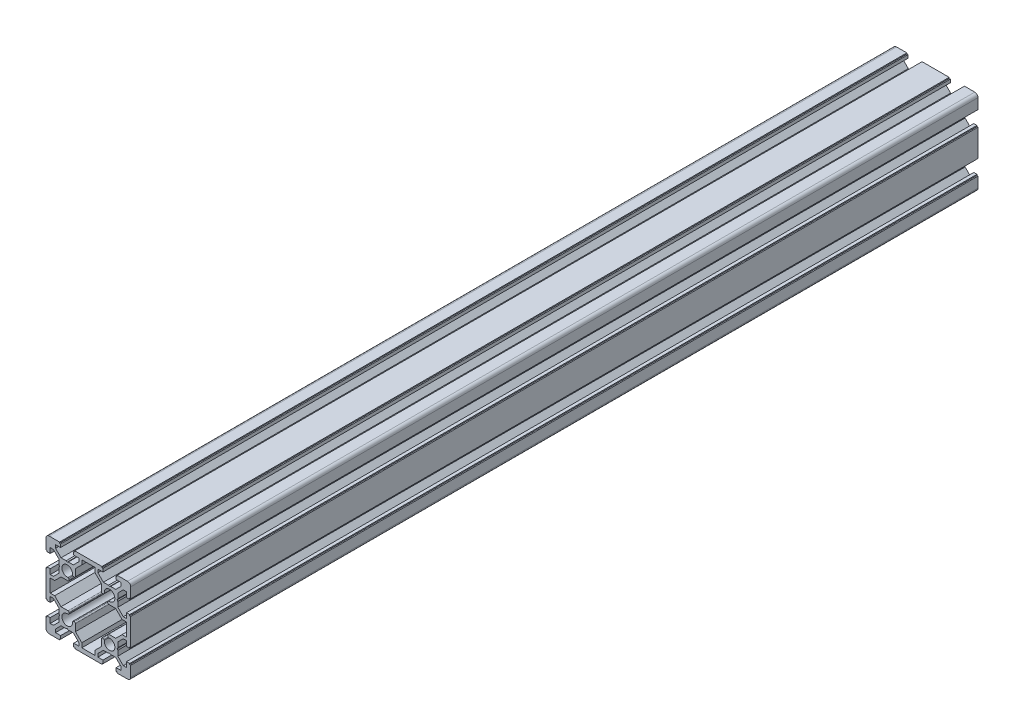
SolidWorks part; units mm, degrees
ref_plane "前视基准面" through (0, 0, 0) normal (0, 0, 1) x (1, 0, 0)
ref_plane "上视基准面" through (0, 0, 0) normal (0, 1, 0) x (1, 0, 0)
ref_plane "右视基准面" through (0, 0, 0) normal (1, 0, 0) x (0, 0, -1)
sketch "草图29" plane through (0, 0, 0) normal (0, 0, 1) x (1, 0, 0)
  line B0 (0, 24.9728) -> (0, 15.0272) construction
  line B1 (-11.0182, 10) -> (30.6964, 10) construction
  line B2 (20, 24.9728) -> (20, 15.0272) construction
  line B3 (20, 4.9728) -> (20, -4.9728) construction
  line B4 (15.0272, 0) -> (24.9728, 0) construction
  line B5 (0, 4.9728) -> (0, -4.9728) construction
  line B6 (-4.9728, 0) -> (4.9728, 0) construction
  line B7 (15.0272, 20) -> (24.9728, 20) construction
  line B8 (-4.9728, 20) -> (4.9728, 20) construction
  line B9 (28, 6.9) -> (25.9101, 6.9)
  line B10 (25.9101, 6.9) -> (22.9101, 3.9)
  line B11 (22.9101, 3.9) -> (19.6066, 3.9)
  line B12 (19.1236, 3.2706) -> (19.2795, 2.689)
  line B13 (17.311, 0.7205) -> (16.7294, 0.8764)
  line B14 (16.1, 0.3934) -> (16.1, -2.9101)
  line B15 (16.1, -2.9101) -> (13.1, -5.9101)
  line B16 (13.1, -5.9101) -> (13.1, -8)
  line B17 (13.1, -8) -> (6.9, -8)
  line B18 (6.9, -8) -> (6.9, -5.9101)
  line B19 (6.9, -5.9101) -> (3.9, -2.9101)
  line B20 (3.9, -2.9101) -> (3.9, 0.3934)
  line B21 (3.2706, 0.8764) -> (2.689, 0.7205)
  line B22 (0.7205, 2.689) -> (0.8764, 3.2706)
  line B23 (0.3934, 3.9) -> (-2.9101, 3.9)
  line B24 (-2.9101, 3.9) -> (-5.9101, 6.9)
  line B25 (-5.9101, 6.9) -> (-8, 6.9)
  line B26 (-8, 6.9) -> (-8, 13.1)
  line B27 (-8, 13.1) -> (-5.9101, 13.1)
  line B28 (-5.9101, 13.1) -> (-2.9101, 16.1)
  line B29 (-2.9101, 16.1) -> (0.3934, 16.1)
  line B30 (0.8764, 16.7294) -> (0.7205, 17.311)
  line B31 (2.689, 19.2795) -> (3.2706, 19.1236)
  line B32 (3.9, 19.6066) -> (3.9, 22.9101)
  line B33 (3.9, 22.9101) -> (6.9, 25.9101)
  line B34 (6.9, 25.9101) -> (6.9, 28)
  line B35 (6.9, 28) -> (13.1, 28)
  line B36 (13.1, 28) -> (13.1, 25.9101)
  line B37 (13.1, 25.9101) -> (16.1, 22.9101)
  line B38 (16.1, 22.9101) -> (16.1, 19.6066)
  line B39 (16.7294, 19.1236) -> (17.311, 19.2795)
  line B40 (19.2795, 17.311) -> (19.1236, 16.7294)
  line B41 (19.6066, 16.1) -> (22.9101, 16.1)
  line B42 (22.9101, 16.1) -> (25.9101, 13.1)
  line B43 (25.9101, 13.1) -> (28, 13.1)
  line B44 (28, 13.1) -> (28, 6.9)
  line B45 (0.5196, -3.9) -> (2.9101, -3.9)
  line B46 (2.9101, -3.9) -> (5.5, -6.4899)
  line B47 (5.5, -6.4899) -> (5.5, -8)
  line B48 (5.5, -8) -> (3.1, -8)
  line B49 (3.1, -8) -> (3.1, -9.5)
  line B50 (3.1, -9.5) -> (3.6, -9.5)
  line B51 (3.6, -9.5) -> (3.6, -10)
  line B52 (3.6, -10) -> (16.4, -10)
  line B53 (16.4, -10) -> (16.4, -9.5)
  line B54 (16.4, -9.5) -> (16.9, -9.5)
  line B55 (16.9, -9.5) -> (16.9, -8)
  line B56 (16.9, -8) -> (14.5, -8)
  line B57 (14.5, -8) -> (14.5, -6.4899)
  line B58 (14.5, -6.4899) -> (17.0899, -3.9)
  line B59 (17.0899, -3.9) -> (19.4804, -3.9)
  line B60 (19.4804, -3.9) -> (20, -3.6)
  line B61 (20, -3.6) -> (20.5196, -3.9)
  line B62 (20.5196, -3.9) -> (22.9101, -3.9)
  line B63 (22.9101, -3.9) -> (25.5, -6.4899)
  line B64 (25.5, -6.4899) -> (25.5, -8)
  line B65 (25.5, -8) -> (23.1, -8)
  line B66 (23.1, -8) -> (23.1, -9.5)
  line B67 (23.1, -9.5) -> (23.6, -9.5)
  line B68 (23.6, -9.5) -> (23.6, -10)
  line B69 (23.6, -10) -> (28.5, -10)
  line B70 (30, -8.5) -> (30, -3.6)
  line B71 (30, -3.6) -> (29.5, -3.6)
  line B72 (29.5, -3.6) -> (29.5, -3.1)
  line B73 (29.5, -3.1) -> (28, -3.1)
  line B74 (28, -3.1) -> (28, -5.5)
  line B75 (28, -5.5) -> (26.4899, -5.5)
  line B76 (26.4899, -5.5) -> (23.9, -2.9101)
  line B77 (23.9, -2.9101) -> (23.9, -0.5196)
  line B78 (23.9, -0.5196) -> (23.6, 0)
  line B79 (23.6, 0) -> (23.9, 0.5196)
  line B80 (23.9, 0.5196) -> (23.9, 2.9101)
  line B81 (23.9, 2.9101) -> (26.4899, 5.5)
  line B82 (26.4899, 5.5) -> (28, 5.5)
  line B83 (28, 5.5) -> (28, 3.1)
  line B84 (28, 3.1) -> (29.5, 3.1)
  line B85 (29.5, 3.1) -> (29.5, 3.6)
  line B86 (29.5, 3.6) -> (30, 3.6)
  line B87 (30, 3.6) -> (30, 16.4)
  line B88 (30, 16.4) -> (29.5, 16.4)
  line B89 (29.5, 16.4) -> (29.5, 16.9)
  line B90 (29.5, 16.9) -> (28, 16.9)
  line B91 (28, 16.9) -> (28, 14.5)
  line B92 (28, 14.5) -> (26.4899, 14.5)
  line B93 (26.4899, 14.5) -> (23.9, 17.0899)
  line B94 (23.9, 17.0899) -> (23.9, 19.4804)
  line B95 (23.9, 19.4804) -> (23.6, 20)
  line B96 (23.6, 20) -> (23.9, 20.5196)
  line B97 (23.9, 20.5196) -> (23.9, 22.9101)
  line B98 (23.9, 22.9101) -> (26.4899, 25.5)
  line B99 (26.4899, 25.5) -> (28, 25.5)
  line B100 (28, 25.5) -> (28, 23.1)
  line B101 (28, 23.1) -> (29.5, 23.1)
  line B102 (29.5, 23.1) -> (29.5, 23.6)
  line B103 (29.5, 23.6) -> (30, 23.6)
  line B104 (30, 23.6) -> (30, 28.5)
  line B105 (28.5, 30) -> (23.6, 30)
  line B106 (23.6, 30) -> (23.6, 29.5)
  line B107 (23.6, 29.5) -> (23.1, 29.5)
  line B108 (23.1, 29.5) -> (23.1, 28)
  line B109 (23.1, 28) -> (25.5, 28)
  line B110 (25.5, 28) -> (25.5, 26.4899)
  line B111 (25.5, 26.4899) -> (22.9101, 23.9)
  line B112 (22.9101, 23.9) -> (20.5196, 23.9)
  line B113 (20.5196, 23.9) -> (20, 23.6)
  line B114 (20, 23.6) -> (19.4804, 23.9)
  line B115 (19.4804, 23.9) -> (17.0899, 23.9)
  line B116 (17.0899, 23.9) -> (14.5, 26.4899)
  line B117 (14.5, 26.4899) -> (14.5, 28)
  line B118 (14.5, 28) -> (16.9, 28)
  line B119 (16.9, 28) -> (16.9, 29.5)
  line B120 (16.9, 29.5) -> (16.4, 29.5)
  line B121 (16.4, 29.5) -> (16.4, 30)
  line B122 (16.4, 30) -> (3.6, 30)
  line B123 (3.6, 30) -> (3.6, 29.5)
  line B124 (3.6, 29.5) -> (3.1, 29.5)
  line B125 (3.1, 29.5) -> (3.1, 28)
  line B126 (3.1, 28) -> (5.5, 28)
  line B127 (5.5, 28) -> (5.5, 26.4899)
  line B128 (5.5, 26.4899) -> (2.9101, 23.9)
  line B129 (2.9101, 23.9) -> (0.5196, 23.9)
  line B130 (0.5196, 23.9) -> (0, 23.6)
  line B131 (0, 23.6) -> (-0.5196, 23.9)
  line B132 (-0.5196, 23.9) -> (-2.9101, 23.9)
  line B133 (-2.9101, 23.9) -> (-5.5, 26.4899)
  line B134 (-5.5, 26.4899) -> (-5.5, 28)
  line B135 (-5.5, 28) -> (-3.1, 28)
  line B136 (-3.1, 28) -> (-3.1, 29.5)
  line B137 (-3.1, 29.5) -> (-3.6, 29.5)
  line B138 (-3.6, 29.5) -> (-3.6, 30)
  line B139 (-3.6, 30) -> (-8.5, 30)
  line B140 (-10, 28.5) -> (-10, 23.6)
  line B141 (-10, 23.6) -> (-9.5, 23.6)
  line B142 (-9.5, 23.6) -> (-9.5, 23.1)
  line B143 (-9.5, 23.1) -> (-8, 23.1)
  line B144 (-8, 23.1) -> (-8, 25.5)
  line B145 (-8, 25.5) -> (-6.4899, 25.5)
  line B146 (-6.4899, 25.5) -> (-3.9, 22.9101)
  line B147 (-3.9, 22.9101) -> (-3.9, 20.5196)
  line B148 (-3.9, 20.5196) -> (-3.6, 20)
  line B149 (-3.6, 20) -> (-3.9, 19.4804)
  line B150 (-3.9, 19.4804) -> (-3.9, 17.0899)
  line B151 (-3.9, 17.0899) -> (-6.4899, 14.5)
  line B152 (-6.4899, 14.5) -> (-8, 14.5)
  line B153 (-8, 14.5) -> (-8, 16.9)
  line B154 (-8, 16.9) -> (-9.5, 16.9)
  line B155 (-9.5, 16.9) -> (-9.5, 16.4)
  line B156 (-9.5, 16.4) -> (-10, 16.4)
  line B157 (-10, 16.4) -> (-10, 3.6)
  line B158 (-10, 3.6) -> (-9.5, 3.6)
  line B159 (-9.5, 3.6) -> (-9.5, 3.1)
  line B160 (-9.5, 3.1) -> (-8, 3.1)
  line B161 (-8, 3.1) -> (-8, 5.5)
  line B162 (-8, 5.5) -> (-6.4899, 5.5)
  line B163 (-6.4899, 5.5) -> (-3.9, 2.9101)
  line B164 (-3.9, 2.9101) -> (-3.9, 0.5196)
  line B165 (-3.9, 0.5196) -> (-3.6, 0)
  line B166 (-3.6, 0) -> (-3.9, -0.5196)
  line B167 (-3.9, -0.5196) -> (-3.9, -2.9101)
  line B168 (-3.9, -2.9101) -> (-6.4899, -5.5)
  line B169 (-6.4899, -5.5) -> (-8, -5.5)
  line B170 (-8, -5.5) -> (-8, -3.1)
  line B171 (-8, -3.1) -> (-9.5, -3.1)
  line B172 (-9.5, -3.1) -> (-9.5, -3.6)
  line B173 (-9.5, -3.6) -> (-10, -3.6)
  line B174 (-10, -3.6) -> (-10, -8.5)
  line B175 (-8.5, -10) -> (-3.6, -10)
  line B176 (-3.6, -10) -> (-3.6, -9.5)
  line B177 (-3.6, -9.5) -> (-3.1, -9.5)
  line B178 (-3.1, -9.5) -> (-3.1, -8)
  line B179 (-3.1, -8) -> (-5.5, -8)
  line B180 (-5.5, -8) -> (-5.5, -6.4899)
  line B181 (-5.5, -6.4899) -> (-2.9101, -3.9)
  line B182 (-2.9101, -3.9) -> (-0.5196, -3.9)
  line B183 (-0.5196, -3.9) -> (0, -3.6)
  line B184 (0, -3.6) -> (0.5196, -3.9)
  line B185 (10, -12.3818) -> (10, 32) construction
  arc B186 (19.6066, 3.9) -> (19.1236, 3.2706) centre (19.6066, 3.4) ccw
  arc B187 (19.2795, 2.689) -> (19.6154, 2.4702) centre (19.5693, 2.7667) ccw
  arc B188 (17.5298, 0.3846) -> (19.6154, 2.4702) centre (20, 0) ccw
  arc B189 (17.5298, 0.3846) -> (17.311, 0.7205) centre (17.2333, 0.4307) ccw
  arc B190 (16.7294, 0.8764) -> (16.1, 0.3934) centre (16.6, 0.3934) ccw
  arc B191 (3.9, 0.3934) -> (3.2706, 0.8764) centre (3.4, 0.3934) ccw
  arc B192 (2.689, 0.7205) -> (2.4702, 0.3846) centre (2.7667, 0.4307) ccw
  arc B193 (0.3846, 2.4702) -> (2.4702, 0.3846) centre (0, 0) ccw
  arc B194 (0.3846, 2.4702) -> (0.7205, 2.689) centre (0.4307, 2.7667) ccw
  arc B195 (0.8764, 3.2706) -> (0.3934, 3.9) centre (0.3934, 3.4) ccw
  arc B196 (0.3934, 16.1) -> (0.8764, 16.7294) centre (0.3934, 16.6) ccw
  arc B197 (0.7205, 17.311) -> (0.3846, 17.5298) centre (0.4307, 17.2333) ccw
  arc B198 (2.4702, 19.6154) -> (0.3846, 17.5298) centre (0, 20) ccw
  arc B199 (2.4702, 19.6154) -> (2.689, 19.2795) centre (2.7667, 19.5693) ccw
  arc B200 (3.2706, 19.1236) -> (3.9, 19.6066) centre (3.4, 19.6066) ccw
  arc B201 (16.1, 19.6066) -> (16.7294, 19.1236) centre (16.6, 19.6066) ccw
  arc B202 (17.311, 19.2795) -> (17.5298, 19.6154) centre (17.2333, 19.5693) ccw
  arc B203 (19.6154, 17.5298) -> (17.5298, 19.6154) centre (20, 20) ccw
  arc B204 (19.6154, 17.5298) -> (19.2795, 17.311) centre (19.5693, 17.2333) ccw
  arc B205 (19.1236, 16.7294) -> (19.6066, 16.1) centre (19.6066, 16.6) ccw
  arc B206 (28.5, -10) -> (30, -8.5) centre (28.5, -8.5) ccw
  arc B207 (30, 28.5) -> (28.5, 30) centre (28.5, 28.5) ccw
  arc B208 (-8.5, 30) -> (-10, 28.5) centre (-8.5, 28.5) ccw
  arc B209 (-10, -8.5) -> (-8.5, -10) centre (-8.5, -8.5) ccw
sketch_block_instance "块2-1"
sketch_block "块2"
extrude "凸台-拉伸1" add sketch "草图29" along normal blind 400
cosmetic thread "装饰螺纹线1" [suppressed]
cosmetic thread "装饰螺纹线2" [suppressed]
cosmetic thread "装饰螺纹线3" [suppressed]
cosmetic thread "装饰螺纹线4" [suppressed]
cosmetic thread "装饰螺纹线5" [suppressed]
cosmetic thread "装饰螺纹线6" [suppressed]
cosmetic thread "装饰螺纹线7" [suppressed]
cosmetic thread "装饰螺纹线8" [suppressed]
ref_plane "基准面1" through (0, 0, 400) normal (0, 0, 1) x (1, 0, 0)
ref_plane "基准面2" through (0, 30, 0) normal (0, 1, 0) x (1, 0, 0)
ref_plane "基准面3" through (0, -10, 0) normal (0, 1, 0) x (1, 0, 0)
ref_plane "基准面4" through (30, 0, 0) normal (1, 0, 0) x (0, 0, -1)
ref_plane "基准面5" through (-10, 0, 0) normal (1, 0, 0) x (0, 0, -1)
sketch "草图19" plane through (0, 0, 0) normal (0, 0, 1) x (1, 0, 0)
  line L0 (0, 0) -> (0, 11.6901) construction
  line L1 (0, 0) -> (10.3437, 0) construction
sketch "草图20" plane through (0, 0, 0) normal (0, 1, 0) x (1, 0, 0)
  line L0 (0, 0) -> (0, 3.5576) construction
ref_point "点1"
sketch "草图2" [suppressed] plane through (0, 0, 0) normal (1, 0, 0) x (0, 0, -1)
  line L0 (-310, -10) -> (-270, 30)
  line L1 (16.5, -10) -> (-16.5, -10) construction
  line L2 (16.5, 30) -> (-16.5, 30) construction
  line L3 (-270, 30) -> (-310, 30)
  line L4 (-310, 16.5) -> (-310, -16.5) construction
  line L5 (-310, 30) -> (-310, -10)
  dimension "D1" = 45
extrude "切除-拉伸1" [suppressed] cut sketch "草图2" against normal through all and the other way through all
sketch "草图3" [suppressed] plane through (0, 0, 0) normal (1, 0, 0) x (0, 0, -1)
  line L0 (0, -10) -> (-40, 30)
  line L1 (16.5, -10) -> (-16.5, -10) construction
  line L2 (16.5, 30) -> (-16.5, 30) construction
  line L3 (-40, 30) -> (0, 30)
  line L4 (0, 30) -> (0, -10)
  line L5 (0, 22) -> (0, -22) construction
  dimension "D1" = 45
extrude "切除-拉伸2" [suppressed] cut sketch "草图3" against normal through all and the other way through all
sketch "草图4" [suppressed] plane through (0, 0, 0) normal (1, 0, 0) x (0, 0, -1)
  line L0 (-310, 30) -> (-270, -10)
  line L1 (16.5, 30) -> (-16.5, 30) construction
  line L2 (-310, 16.5) -> (-310, -16.5) construction
  line L3 (16.5, -10) -> (-16.5, -10) construction
  line L4 (-270, -10) -> (-310, -10)
  line L5 (-310, -10) -> (-310, 30)
  dimension "D1" = 45
extrude "切除-拉伸3" [suppressed] cut sketch "草图4" against normal through all and the other way through all
sketch "草图5" [suppressed] plane through (0, 0, 0) normal (1, 0, 0) x (0, 0, -1)
  line L0 (0, 30) -> (-40, -10)
  line L1 (16.5, 30) -> (-16.5, 30) construction
  line L2 (16.5, -10) -> (-16.5, -10) construction
  line L3 (-40, -10) -> (0, -10)
  line L4 (0, -10) -> (0, 30)
  line L5 (0, 22) -> (0, -22) construction
  dimension "D1" = 45
extrude "切除-拉伸4" [suppressed] cut sketch "草图5" against normal through all and the other way through all
sketch "草图6" [suppressed] plane through (0, 0, 0) normal (0, 1, 0) x (1, 0, 0)
  line L0 (-10, -310) -> (30, -270)
  line L1 (-10, -16.5) -> (-10, 16.5) construction
  line L2 (-16.5, -310) -> (16.5, -310) construction
  line L3 (30, -16.5) -> (30, 16.5) construction
  line L4 (30, -270) -> (30, -310)
  line L5 (30, -310) -> (-10, -310)
  dimension "D1" = 45
extrude "切除-拉伸5" [suppressed] cut sketch "草图6" against normal through all and the other way through all
sketch "草图7" [suppressed] plane through (0, 0, 0) normal (0, 1, 0) x (1, 0, 0)
  line L0 (-10, 0) -> (30, -40)
  line L1 (-10, -16.5) -> (-10, 16.5) construction
  line L2 (30, -16.5) -> (30, 16.5) construction
  line L3 (30, -40) -> (30, 0)
  line L4 (-22, 0) -> (22, 0) construction
  line L5 (30, 0) -> (-10, 0)
  dimension "D1" = 45
extrude "切除-拉伸6" [suppressed] cut sketch "草图7" against normal through all and the other way through all
sketch "草图8" [suppressed] plane through (0, 0, 0) normal (0, 1, 0) x (1, 0, 0)
  line L0 (-10, -270) -> (30, -310)
  line L1 (-10, -22) -> (-10, 22) construction
  line L2 (30, -22) -> (30, 22) construction
  line L3 (-22, -310) -> (22, -310) construction
  line L4 (30, -310) -> (-10, -310)
  line L5 (-10, -310) -> (-10, -270)
  dimension "D1" = 45
extrude "切除-拉伸7" [suppressed] cut sketch "草图8" against normal through all and the other way through all
sketch "草图9" [suppressed] plane through (0, 0, 0) normal (0, 1, 0) x (1, 0, 0)
  line L0 (30, 0) -> (-10, -40)
  line L1 (30, -22) -> (30, 22) construction
  line L2 (-22, 0) -> (22, 0) construction
  line L3 (-10, -22) -> (-10, 22) construction
  line L4 (-10, -40) -> (-10, 0)
  line L5 (-10, 0) -> (30, 0)
  dimension "D1" = 45
extrude "切除-拉伸8" [suppressed] cut sketch "草图9" against normal through all and the other way through all
sketch "草图10" [suppressed] plane through (30, -3.64, 139.7) normal (1, 0, 0) x (0, 0, -1)
  line L1 (-170.3, 25.64) -> (-170.3, -18.36) construction
  circle A0 centre (-157.3, 3.64) radius 6.25
  dimension "D1" = 12.5
  dimension "D2" = 13
extrude "切除-拉伸9" [suppressed] cut sketch "草图10" against normal blind 9
pattern_linear "阵列(线性)1" [suppressed] count 2 spacing 20 along (0, 1, 0)
sketch "草图11" [suppressed] plane through (30, 0, 0) normal (1, 0, 0) x (0, 0, -1)
  circle A0 centre (-13, 0) radius 6.25
  dimension "D1" = 12.5
  dimension "D2" = 13
extrude "切除-拉伸10" [suppressed] cut sketch "草图11" against normal blind 9
pattern_linear "阵列(线性)2" [suppressed] count 2 spacing 20 along (0, 1, 0)
sketch "草图12" [suppressed] plane through (0, 0, 0) normal (0, 1, 0) x (1, 0, 0)
  line L0 (-10, -22) -> (-10, 22) construction
  line L1 (-10, -297) -> (-1, -297)
  line L2 (-10, -297) -> (-10, -290.75)
  line L3 (-10, -290.75) -> (-1, -290.75)
  line L4 (-1, -297) -> (-1, -290.75)
  line L5 (30, -22) -> (30, 22) construction
  line L6 (30, -297) -> (21, -297)
  line L7 (30, -297) -> (30, -290.75)
  line L8 (30, -290.75) -> (21, -290.75)
  line L9 (21, -297) -> (21, -290.75)
  line L10 (-22, -310) -> (22, -310) construction
  dimension "D1" = 13
  dimension "D2" = 6.25
  dimension "D3" = 9
revolve "切除-旋转1" [suppressed] cut sketch "草图12" angle 360 about L1
pattern_linear "阵列(线性)4" [suppressed] count 2 spacing 20 along (0, 1, 0)
sketch "草图13" [suppressed] plane through (0, 0, 0) normal (0, 1, 0) x (1, 0, 0)
  line L0 (-10, -22) -> (-10, 22) construction
  line L1 (-10, -19.25) -> (-1, -19.25)
  line L2 (-10, -19.25) -> (-10, -13)
  line L3 (-10, -13) -> (-1, -13)
  line L4 (-1, -19.25) -> (-1, -13)
  line L5 (30, -22) -> (30, 22) construction
  line L6 (30, -19.25) -> (21, -19.25)
  line L7 (30, -19.25) -> (30, -13)
  line L8 (30, -13) -> (21, -13)
  line L9 (21, -19.25) -> (21, -13)
  dimension "D1" = 13
  dimension "D2" = 6.25
  dimension "D3" = 9
revolve "切除-旋转2" [suppressed] cut sketch "草图13" angle 360 about L3
pattern_linear "阵列(线性)5" [suppressed] count 2 spacing 20 along (0, 1, 0)
sketch "草图14" [suppressed] plane through (0, 30, 0) normal (0, 1, 0) x (1, 0, 0)
  line L0 (-22, -310) -> (22, -310) construction
  circle A0 centre (0, -297) radius 6.25
  dimension "D1" = 12.5
  dimension "D2" = 13
extrude "切除-拉伸11" [suppressed] cut sketch "草图14" against normal blind 9
pattern_linear "阵列(线性)10" [suppressed] count 2 spacing 20 along (1, 0, 0)
sketch "草图15" [suppressed] plane through (0, 30, 0) normal (0, 1, 0) x (1, 0, 0)
  line L0 (-22, 0) -> (22, 0) construction
  circle A0 centre (0, -13) radius 6.25
  dimension "D1" = 12.5
  dimension "D2" = 13
extrude "切除-拉伸12" [suppressed] cut sketch "草图15" against normal blind 9
pattern_linear "阵列(线性)11" [suppressed] count 2 spacing 20 along (1, 0, 0)
sketch "草图16" [suppressed] plane through (0, 0, 0) normal (1, 0, 0) x (0, 0, -1)
  line L0 (22, 30) -> (-22, 30) construction
  line L1 (-297, 30) -> (-290.75, 30)
  line L2 (-297, 30) -> (-297, 21)
  line L3 (-297, 21) -> (-290.75, 21)
  line L4 (-290.75, 30) -> (-290.75, 21)
  line L5 (22, -10) -> (-22, -10) construction
  line L6 (-297, -10) -> (-290.75, -10)
  line L7 (-297, -10) -> (-297, -1)
  line L8 (-297, -1) -> (-290.75, -1)
  line L9 (-290.75, -10) -> (-290.75, -1)
  line L10 (-310, 22) -> (-310, -22) construction
  dimension "D1" = 9
  dimension "D2" = 6.25
  dimension "D3" = 13
revolve "切除-旋转3" [suppressed] cut sketch "草图16" angle 360 about L2
pattern_linear "阵列(线性)12" [suppressed] count 2 spacing 20 along (1, 0, 0)
sketch "草图17" [suppressed] plane through (0, 0, 0) normal (1, 0, 0) x (0, 0, -1)
  line L0 (22, 30) -> (-22, 30) construction
  line L1 (-13, 30) -> (-19.25, 30)
  line L2 (-13, 30) -> (-13, 21)
  line L3 (-13, 21) -> (-19.25, 21)
  line L4 (-19.25, 30) -> (-19.25, 21)
  line L5 (22, -10) -> (-22, -10) construction
  line L6 (-13, -10) -> (-19.25, -10)
  line L7 (-13, -10) -> (-13, -1)
  line L8 (-13, -1) -> (-19.25, -1)
  line L9 (-19.25, -10) -> (-19.25, -1)
  dimension "D1" = 6.25
  dimension "D2" = 9
  dimension "D3" = 13
revolve "切除-旋转4" [suppressed] cut sketch "草图17" angle 360 about L2
pattern_linear "阵列(线性)13" [suppressed] count 2 spacing 20 along (1, 0, 0)
sketch "草图18" [suppressed] plane through (0, 0, 0) normal (0, 1, 0) x (1, 0, 0)
  line L0 (-10, -250) -> (30, -250)
  line L1 (-10, -22) -> (-10, 22) construction
  line L2 (30, -22) -> (30, 22) construction
  line L3 (30, -250) -> (30, -244.5)
  line L4 (30, -244.5) -> (23.5, -244.5)
  line L5 (23.5, -244.5) -> (23.5, -246.75)
  line L6 (23.5, -246.75) -> (-10, -246.75)
  line L7 (-10, -246.75) -> (-10, -250)
  line L8 (-22, -310) -> (22, -310) construction
  dimension "D1" = 60
  dimension "D2" = 5.5
  dimension "D3" = 3.25
  dimension "D4" = 6.5
revolve "切除-旋转5" [suppressed] cut sketch "草图18" angle 360 about L0
pattern_linear "阵列(线性)6" [suppressed] count 2 spacing 20 along (0, 1, 0)
other "表格阵列1" [suppressed] parameters "D0"=20, "D1"=0, "D2"=40, "D3"=0, "D4"=60, "D5"=0, "D6"=80, "D7"=0
sketch "草图21" [suppressed] plane through (0, 0, 0) normal (0, 1, 0) x (1, 0, 0)
  line L0 (-10, -60) -> (30, -60)
  line L1 (-10, -22) -> (-10, 22) construction
  line L2 (30, -22) -> (30, 22) construction
  line L3 (30, -60) -> (30, -65.5)
  line L4 (30, -65.5) -> (23.5, -65.5)
  line L5 (23.5, -65.5) -> (23.5, -63.25)
  line L6 (23.5, -63.25) -> (-10, -63.25)
  line L7 (-10, -63.25) -> (-10, -60)
  dimension "D1" = 5.5
  dimension "D2" = 3.25
  dimension "D3" = 6.5
  dimension "D4" = 60
revolve "切除-旋转6" [suppressed] cut sketch "草图21" angle 360 about L0
pattern_linear "阵列(线性)7" [suppressed] count 2 spacing 20 along (0, 1, 0)
other "表格阵列2" [suppressed] parameters "D0"=20, "D1"=0, "D2"=40, "D3"=0, "D4"=60, "D5"=0, "D6"=80, "D7"=0
sketch "草图22" [suppressed] plane through (0, 0, 0) normal (1, 0, 0) x (0, 0, -1)
  line L0 (-250, 30) -> (-250, -10)
  line L1 (22, 30) -> (-22, 30) construction
  line L2 (22, -10) -> (-22, -10) construction
  line L3 (-250, -10) -> (-246.75, -10)
  line L4 (-246.75, -10) -> (-246.75, 23.5)
  line L5 (-246.75, 23.5) -> (-244.5, 23.5)
  line L6 (-244.5, 23.5) -> (-244.5, 30)
  line L7 (-244.5, 30) -> (-250, 30)
  line L8 (-310, 22) -> (-310, -22) construction
  dimension "D1" = 5.5
  dimension "D2" = 3.25
  dimension "D3" = 6.5
  dimension "D4" = 60
revolve "切除-旋转7" [suppressed] cut sketch "草图22" angle 360 about L0
pattern_linear "阵列(线性)14" [suppressed] count 2 spacing 20 along (1, 0, 0)
other "表格阵列3" [suppressed] parameters "D0"=20, "D1"=0, "D2"=40, "D3"=0, "D4"=60, "D5"=0, "D6"=80, "D7"=0
sketch "草图23" [suppressed] plane through (0, 0, 0) normal (1, 0, 0) x (0, 0, -1)
  line L0 (-60, 30) -> (-65.5, 30)
  line L1 (22, 30) -> (-22, 30) construction
  line L2 (-65.5, 30) -> (-65.5, 23.5)
  line L3 (-65.5, 23.5) -> (-63.25, 23.5)
  line L4 (-63.25, 23.5) -> (-63.25, -10)
  line L5 (22, -10) -> (-22, -10) construction
  line L6 (-63.25, -10) -> (-60, -10)
  line L7 (-60, -10) -> (-60, 30)
  dimension "D1" = 5.5
  dimension "D2" = 3.25
  dimension "D3" = 6.5
  dimension "D4" = 60
revolve "切除-旋转8" [suppressed] cut sketch "草图23" angle 360 about L7
pattern_linear "阵列(线性)15" [suppressed] count 2 spacing 20 along (1, 0, 0)
other "表格阵列4" [suppressed] parameters "D0"=20, "D1"=0, "D2"=40, "D3"=0, "D4"=60, "D5"=0, "D6"=80, "D7"=0
sketch "草图24" [suppressed] plane through (30, 0, 0) normal (1, 0, 0) x (0, 0, -1)
  line L0 (-310, 22) -> (-310, -22) construction
  circle A0 centre (-260, 0) radius 3.25
  dimension "D1" = 6.5
  dimension "D2" = 50
extrude "切除-拉伸13" [suppressed] cut sketch "草图24" against normal through all
pattern_linear "阵列(线性)8" [suppressed] count 2 spacing 20 along (0, 1, 0)
other "表格阵列5" [suppressed] parameters "D0"=70, "D1"=10, "D2"=90, "D3"=10, "D4"=110, "D5"=10, "D6"=130, "D7"=10
sketch "草图25" [suppressed] plane through (30, 0, 0) normal (1, 0, 0) x (0, 0, -1)
  circle A0 centre (-50, 0) radius 3.25
  dimension "D1" = 6.5
  dimension "D2" = 50
extrude "切除-拉伸14" [suppressed] cut sketch "草图25" against normal through all
pattern_linear "阵列(线性)9" [suppressed] count 2 spacing 20 along (0, 1, 0)
other "表格阵列6" [suppressed] parameters "D0"=70, "D1"=10, "D2"=90, "D3"=10, "D4"=110, "D5"=10, "D6"=130, "D7"=10
sketch "草图26" [suppressed] plane through (0, 30, 0) normal (0, 1, 0) x (1, 0, 0)
  line L0 (-22, -310) -> (22, -310) construction
  circle A0 centre (0, -260) radius 3.25
  dimension "D1" = 6.5
  dimension "D2" = 50
extrude "切除-拉伸15" [suppressed] cut sketch "草图26" against normal through all
pattern_linear "阵列(线性)16" [suppressed] count 2 spacing 20 along (1, 0, 0)
other "表格阵列7" [suppressed] parameters "D0"=70, "D1"=10, "D2"=90, "D3"=10, "D4"=110, "D5"=10, "D6"=130, "D7"=10
sketch "草图27" [suppressed] plane through (0, 30, 0) normal (0, 1, 0) x (1, 0, 0)
  circle A0 centre (0, -50) radius 3.25
  dimension "D1" = 6.5
  dimension "D2" = 50
extrude "切除-拉伸16" [suppressed] cut sketch "草图27" against normal through all
pattern_linear "阵列(线性)17" [suppressed] count 2 spacing 20 along (1, 0, 0)
other "表格阵列8" [suppressed] parameters "D0"=70, "D1"=10, "D2"=90, "D3"=10, "D4"=110, "D5"=10, "D6"=130, "D7"=10
sketch "草图30" [suppressed] plane through (0, 0, 0) normal (0, 1, 0) x (1, 0, 0)
  line L0 (-10, -250) -> (-10, -244.5)
  line L1 (-10, -244.5) -> (-3.5, -244.5)
  line L2 (-3.5, -244.5) -> (-3.5, -246.75)
  line L3 (-3.5, -246.75) -> (30, -246.75)
  line L4 (30, -246.75) -> (30, -250)
  line L5 (30, -250) -> (-10, -250)
  line L6 (-10, -22) -> (-10, 22) construction
  line L7 (30, -22) -> (30, 22) construction
  line L8 (-22, -310) -> (22, -310) construction
  dimension "D1" = 3.25
  dimension "D2" = 5.5
  dimension "D3" = 6.5
  dimension "D4" = 60
revolve "切除-旋转9" [suppressed] cut sketch "草图30" angle 360 about L5
pattern_linear "阵列(线性)18" [suppressed] count 2 spacing 20
other "表格阵列9" [suppressed] parameters "D0"=20, "D1"=0, "D2"=40, "D3"=0, "D4"=60, "D5"=0, "D6"=80, "D7"=0
sketch "草图31" [suppressed] plane through (0, 0, 0) normal (0, 1, 0) x (1, 0, 0)
  line L0 (30, -60) -> (30, -63.25)
  line L1 (30, -63.25) -> (-3.5, -63.25)
  line L2 (-3.5, -63.25) -> (-3.5, -65.5)
  line L3 (-3.5, -65.5) -> (-10, -65.5)
  line L4 (-10, -65.5) -> (-10, -60)
  line L5 (-10, -60) -> (30, -60)
  line L6 (-10, -22) -> (-10, 22) construction
  line L7 (30, -22) -> (30, 22) construction
  dimension "D1" = 5.5
  dimension "D2" = 6.5
  dimension "D3" = 3.25
  dimension "D4" = 60
revolve "切除-旋转10" [suppressed] cut sketch "草图31" angle 360 about L5
pattern_linear "阵列(线性)19" [suppressed] count 2 spacing 20
other "表格阵列10" [suppressed] parameters "D0"=20, "D1"=0, "D2"=40, "D3"=0, "D4"=60, "D5"=0, "D6"=80, "D7"=0
sketch "草图32" [suppressed] plane through (0, 0, 0) normal (1, 0, 0) x (0, 0, -1)
  line L0 (-250, 30) -> (-246.75, 30)
  line L1 (-246.75, 30) -> (-246.75, -3.5)
  line L2 (-246.75, -3.5) -> (-244.5, -3.5)
  line L3 (-244.5, -3.5) -> (-244.5, -10)
  line L4 (-244.5, -10) -> (-250, -10)
  line L5 (-250, -10) -> (-250, 30)
  line L6 (22, -10) -> (-22, -10) construction
  line L7 (22, 30) -> (-22, 30) construction
  line L8 (-310, 22) -> (-310, -22) construction
  dimension "D1" = 3.25
  dimension "D2" = 5.5
  dimension "D3" = 6.5
  dimension "D4" = 60
revolve "切除-旋转11" [suppressed] cut sketch "草图32" angle 360 about L5
pattern_linear "阵列(线性)20" [suppressed] count 2 spacing 20 along (1, 0, 0)
other "表格阵列11" [suppressed] parameters "D0"=20, "D1"=0, "D2"=40, "D3"=0, "D4"=60, "D5"=0, "D6"=80, "D7"=0
sketch "草图33" [suppressed] plane through (0, 0, 0) normal (1, 0, 0) x (0, 0, -1)
  line L0 (-60, 30) -> (-63.25, 30)
  line L1 (-63.25, 30) -> (-63.25, -3.5)
  line L2 (-63.25, -3.5) -> (-65.5, -3.5)
  line L3 (-65.5, -3.5) -> (-65.5, -10)
  line L4 (-65.5, -10) -> (-60, -10)
  line L5 (-60, -10) -> (-60, 30)
  line L6 (22, -10) -> (-22, -10) construction
  line L7 (22, 30) -> (-22, 30) construction
  dimension "D1" = 3.25
  dimension "D2" = 5.5
  dimension "D3" = 6.5
  dimension "D4" = 60
revolve "切除-旋转12" [suppressed] cut sketch "草图33" angle 360 about L5
pattern_linear "阵列(线性)21" [suppressed] count 2 spacing 20 along (1, 0, 0)
other "表格阵列12" [suppressed] parameters "D0"=20, "D1"=0, "D2"=40, "D3"=0, "D4"=60, "D5"=0, "D6"=80, "D7"=0
